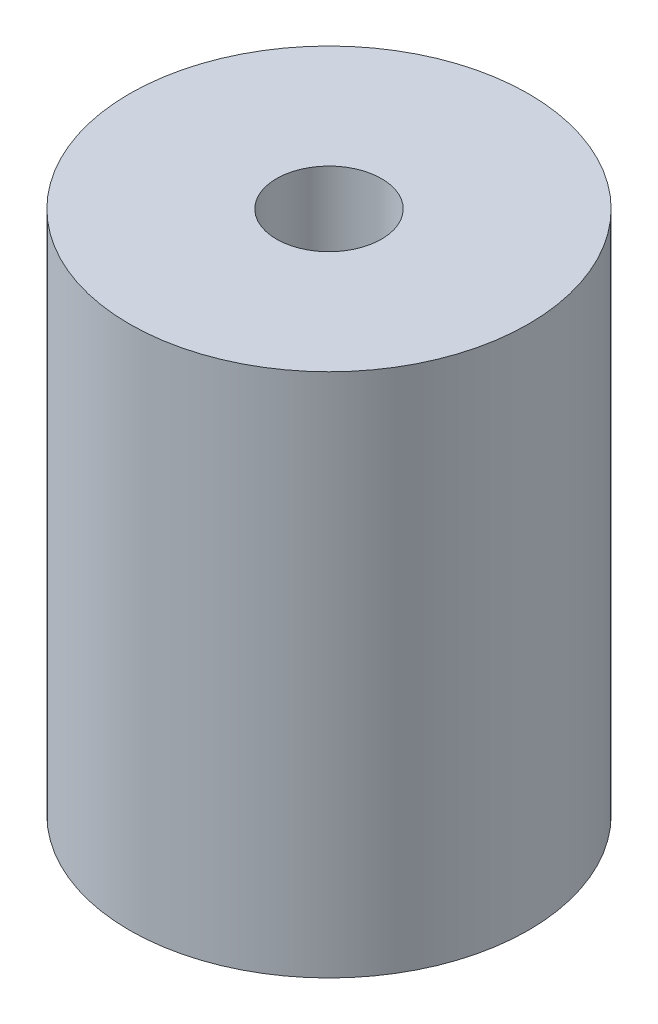
SolidWorks part; units mm, degrees
ref_plane "Front Plane" through (0, 0, 0) normal (0, 0, 1) x (1, 0, 0)
ref_plane "Top Plane" through (0, 0, 0) normal (0, 1, 0) x (1, 0, 0)
ref_plane "Right Plane" through (0, 0, 0) normal (1, 0, 0) x (0, 0, -1)
sketch "Sketch1" plane through (0, 0, 0) normal (0, 1, 0) x (1, 0, 0)
  circle A0 centre (0, 0) radius 9.5
  dimension "D1" = 19
extrude "Boss-Extrude1" add sketch "Sketch1" along normal blind 25
sketch "Sketch2" plane through (0, 25, 0) normal (0, 1, 0) x (1, 0, 0)
  circle A0 centre (0, 0) radius 2.5
  dimension "D1" = 5
extrude "Cut-Extrude1" cut sketch "Sketch2" against normal blind 12.5
sketch "Sketch3" plane through (0, 0, 0) normal (0, -1, 0) x (1, 0, 0)
  circle A0 centre (0, 0) radius 4
  dimension "D1" = 8
extrude "Cut-Extrude2" cut sketch "Sketch3" against normal blind 12.5
